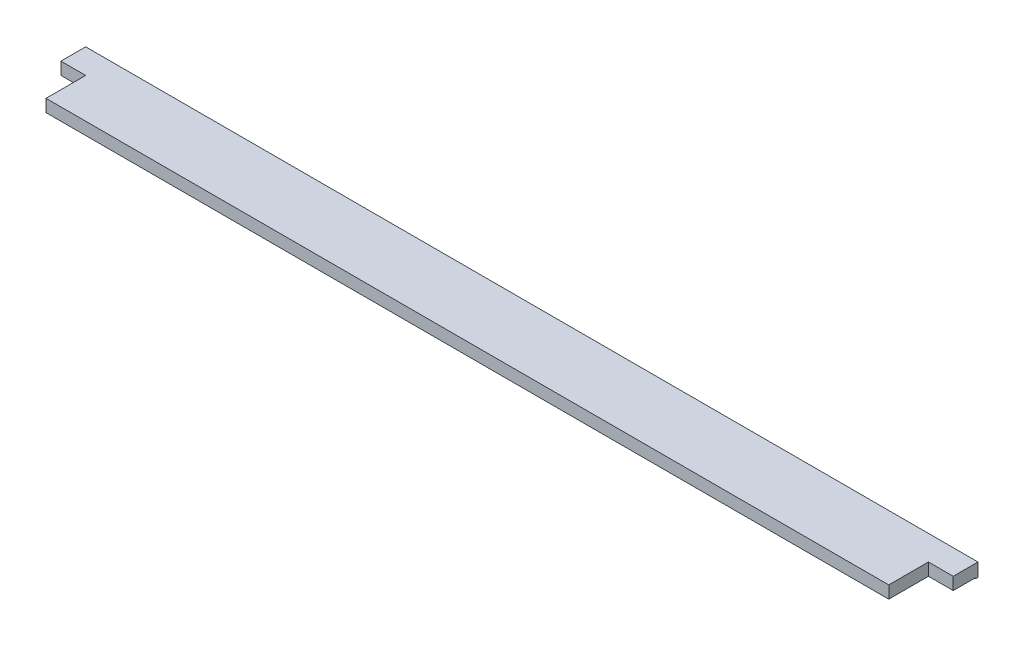
SolidWorks part; units mm, degrees
material "ПВХ Жесткий"
ref_plane "Спереди" through (0, 0, 0) normal (0, 0, 1) x (1, 0, 0)
ref_plane "Сверху" through (0, 0, 0) normal (0, 1, 0) x (1, 0, 0)
ref_plane "Справа" through (0, 0, 0) normal (1, 0, 0) x (0, 0, -1)
other "Configuration Table"
sketch "Эскиз1" plane through (0, 0, 0) normal (1, 0, 0) x (0, 0, -1)
  line L0 (0, 0) -> (130, 0)
  line L1 (130, 0) -> (130, -27)
  line L2 (130, -27) -> (125, -27)
  line L3 (125, -27) -> (125, -25)
  line L4 (125, -25) -> (0, -25)
  line L5 (0, -25) -> (0, 0)
  point P3 (82.09, -27)
  dimension "D1" = 130
  dimension "D2" = 25
  dimension "D3" = 2
  dimension "D4" = 5
extrude "Бобышка-Вытянуть1" add sketch "Эскиз1" along normal blind 1800
sketch "Эскиз2" plane through (0, 0, 0) normal (0, 1, 0) x (1, 0, 0)
  line L1 (0, 0) -> (50, 0)
  line L2 (0, 0) -> (0, 80)
  line L3 (0, 80) -> (50, 80)
  line L4 (50, 0) -> (50, 80)
  line L5 (1800, 0) -> (1750, 0)
  line L6 (1800, 0) -> (1800, 80)
  line L7 (1800, 80) -> (1750, 80)
  line L8 (1750, 0) -> (1750, 80)
  line L9 (1800, 130) -> (0, 130) construction
  dimension "D1" = 50
  dimension "D2" = 50
extrude "Вырез-Вытянуть1" cut sketch "Эскиз2" against normal through all
